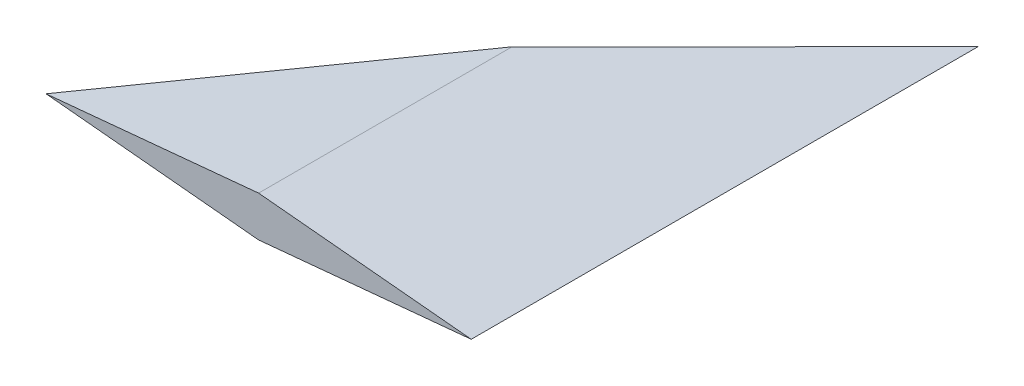
SolidWorks part; units mm, degrees
ref_plane "Front Plane" through (0, 0, 0) normal (0, 0, 1) x (1, 0, 0)
ref_plane "Top Plane" through (0, 0, 0) normal (0, 1, 0) x (1, 0, 0)
ref_plane "Right Plane" through (0, 0, 0) normal (1, 0, 0) x (0, 0, -1)
sketch "Sketch1" plane through (0, 0, 0) normal (0, 1, 0) x (1, 0, 0)
  line L3 (0, 26.8306) -> (0, -4.8852)
  line L4 (0, -4.8852) -> (-26.6127, -4.8852)
  line L5 (-26.6127, -4.8852) -> (0, 26.8306)
  dimension "D1" = 41.402
  dimension "D2" = 40
  dimension "D3" = 90
extrude "Boss-Extrude1" add sketch "Sketch1" along normal blind 2.54
sketch "Sketch2" plane through (0, 0, 4.8852) normal (0, 0, 1) x (1, 0, 0)
  line L0 (-26.6127, 1.27) -> (-13.3063, 2.54)
  line L1 (-26.6127, 2.54) -> (-26.6127, 0) construction
  line L2 (-26.6127, 2.54) -> (0, 2.54) construction
  line L3 (-13.3063, 2.54) -> (0, 1.27)
  line L4 (0, 2.54) -> (0, 0) construction
  line L5 (0, 1.27) -> (-13.3063, 0)
  line L6 (-26.6127, 0) -> (0, 0) construction
  line L7 (-13.3063, 0) -> (-26.6127, 1.27)
  line L8 (-26.6127, 0) -> (-13.3063, 0)
  line L9 (-13.3063, 0) -> (0, 0)
  line L10 (0, 0) -> (0, 1.27)
  line L11 (0, 1.27) -> (0, 2.54)
  line L12 (0, 2.54) -> (-13.3063, 2.54)
  line L13 (-13.3063, 2.54) -> (-26.6127, 2.54)
  line L14 (-26.6127, 2.54) -> (-26.6127, 1.27)
  line M1 (-26.6127, 0) -> (0, 0)
  line M2 (0, 0) -> (0, 2.54)
  line M3 (0, 2.54) -> (-26.6127, 2.54)
  line M4 (-26.6127, 2.54) -> (-26.6127, 0)
extrude "Cut-Extrude1" cut sketch "Sketch2" against normal blind 52.578 contours L0 M4 M3 | L7 M1 M4 | L3 M3 M2 | L5 M2 M1
